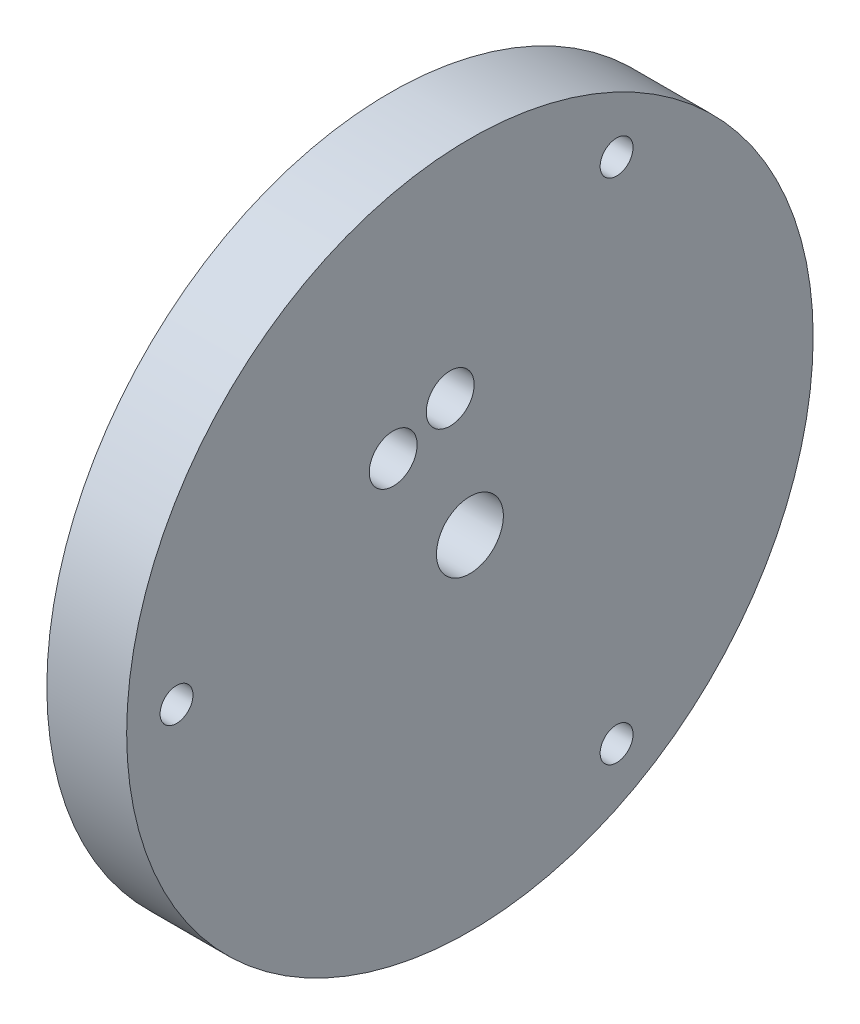
SolidWorks part; units mm, degrees
material "AISI 1010 Steel, hot rolled bar"
ref_plane "Front Plane" through (0, 0, 0) normal (0, 0, 1) x (1, 0, 0)
ref_plane "Top Plane" through (0, 0, 0) normal (0, 1, 0) x (1, 0, 0)
ref_plane "Right Plane" through (0, 0, 0) normal (1, 0, 0) x (0, 0, -1)
sketch "Axial profile (mm)" plane through (0, 0, 0) normal (0, 0, 1) x (1, 0, 0)
  line L0 (-110, 0) -> (75, 0) construction
  line L1 (148.7, 3.35) -> (156.7, 3.35)
  line L2 (156.7, 3.35) -> (156.7, 34.4)
  line L3 (156.7, 34.4) -> (148.7, 34.4)
  line L4 (148.7, 34.4) -> (148.7, 3.35)
revolve "Full revolution" add sketch "Axial profile (mm)" angle 360 about L0
sketch "Sketch2" plane through (0, 0, 0) normal (1, 0, 0) x (0, 0, -1)
  circle A0 centre (-1.9774, 12.8487) radius 2.4
  circle A1 centre (-7.6872, 10.4836) radius 2.4
  circle A2 centre (-29.4, 0) radius 1.65
  circle A3 centre (14.7, -25.4611) radius 1.65
  circle A4 centre (14.7, 25.4611) radius 1.65
extrude "Axial holes" cut sketch "Sketch2" along normal through all and the other way through all
sketch "Sketch3" plane through (0, 0, 0) normal (1, 0, 0) x (0, 0, -1)
  circle A0 centre (-12, 0) radius 1.25
  circle A1 centre (6, -10.3923) radius 1.25
  circle A2 centre (6, 10.3923) radius 1.25
extrude "Cut-Extrude2" cut sketch "Sketch3" along normal blind 6 from offset 148.7
